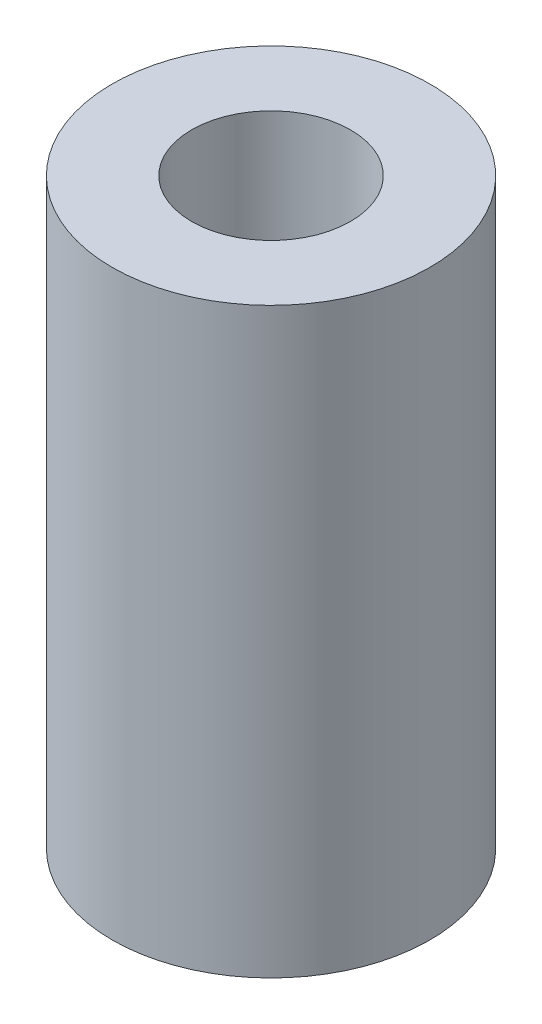
SolidWorks part; units mm, degrees
ref_plane "Front Plane" through (0, 0, 0) normal (0, 0, 1) x (1, 0, 0)
ref_plane "Top Plane" through (0, 0, 0) normal (0, 1, 0) x (1, 0, 0)
ref_plane "Right Plane" through (0, 0, 0) normal (1, 0, 0) x (0, 0, -1)
sketch "Sketch1" plane through (0, 0, 0) normal (0, 1, 0) x (1, 0, 0)
  circle A0 centre (0, 0) radius 3
  circle A1 centre (0, 0) radius 1.5
  dimension "D1" = 6
  dimension "D2" = 3
extrude "Boss-Extrude1" add sketch "Sketch1" along normal blind 11
